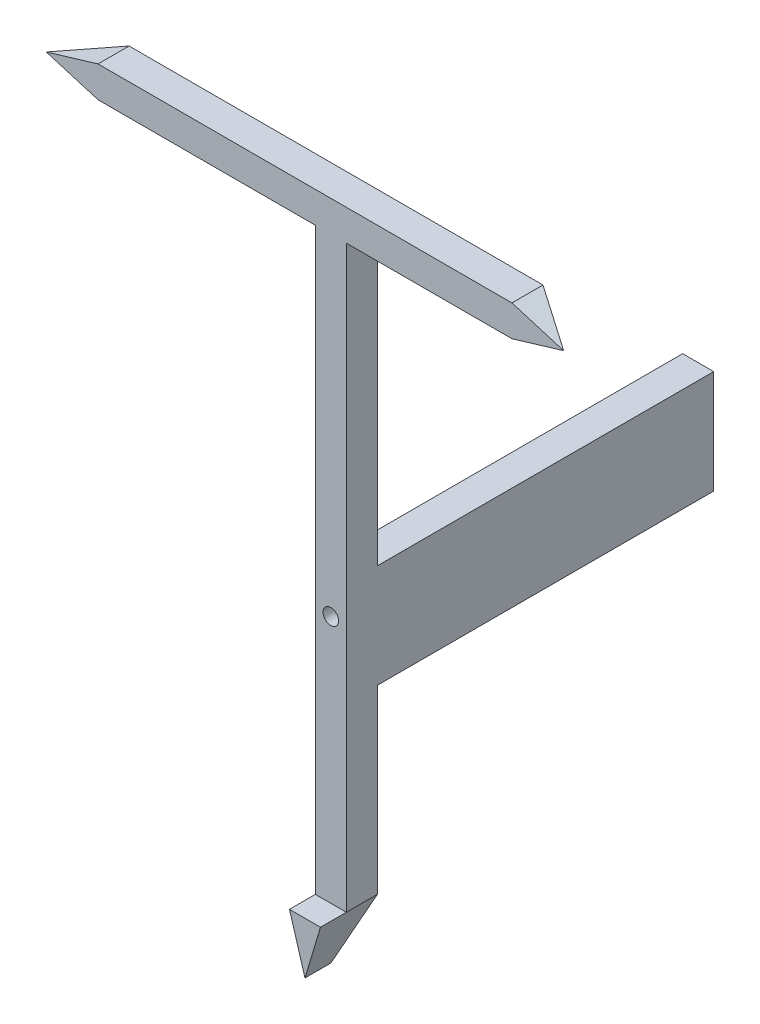
SolidWorks part; units mm, degrees
ref_plane "Front Plane" through (0, 0, 0) normal (0, 0, 1) x (1, 0, 0)
ref_plane "Top Plane" through (0, 0, 0) normal (0, 1, 0) x (1, 0, 0)
ref_plane "Right Plane" through (0, 0, 0) normal (1, 0, 0) x (0, 0, -1)
sketch "Sketch1" plane through (0, 0, 0) normal (0, 0, 1) x (1, 0, 0)
  line L0 (-63.5, 0) -> (63.5, 0) construction
  line L1 (6.35, 0) -> (6.35, -158.75) construction
  line L2 (-63.5, 0) -> (-50.8, 3.81)
  line L3 (-50.8, 3.81) -> (50.8, 3.81)
  line L4 (50.8, 3.81) -> (63.5, 0)
  line L5 (63.5, 0) -> (50.8, -3.81)
  line L6 (50.8, -3.81) -> (10.16, -3.81)
  line L7 (-50.8, -3.81) -> (-63.5, 0)
  line L8 (6.35, -158.75) -> (2.54, -146.05)
  line L9 (6.35, -158.75) -> (10.16, -146.05)
  line L10 (2.54, -146.05) -> (2.54, -3.81)
  line L11 (10.16, -146.05) -> (10.16, -3.81)
  line L12 (2.54, -3.81) -> (-50.8, -3.81)
  circle A0 centre (6.35, -85.09) radius 1.905
  point P2 (0, 0)
  dimension "D12" = 3.81
  dimension "D1" = 127
  dimension "D2" = 69.85
  dimension "D3" = 158.75
  dimension "D4" = 12.7
  dimension "D5" = 12.7
  dimension "D6" = 7.62
  dimension "D7" = 3.81
  dimension "D8" = 12.7
  dimension "D9" = 7.62
  dimension "D10" = 3.81
  dimension "D11" = 88.9
ref_plane "Plane1" through (6.35, 0, 0) normal (1, 0, 0) x (0, 0, -1)
sketch "Sketch2" plane through (6.35, 0, 0) normal (1, 0, 0) x (0, 0, -1)
  line L0 (0, -158.75) -> (-6.35, -158.75)
  dimension "D1" = 6.35
extrude "Boss-Extrude1" add sketch "Sketch1" against normal blind 7.62
sketch "Sketch3" plane through (0, 3.81, 0) normal (0, 1, 0) x (1, 0, 0)
  line L0 (-63.5, 0) -> (-50.8, 7.62)
  line L1 (-50.8, 7.62) -> (-63.5, 7.62)
  line L2 (-63.5, 7.62) -> (-63.5, 0)
  line L3 (63.5, 7.62) -> (63.5, 0)
  line L4 (63.5, 0) -> (50.8, 7.62)
  line L5 (50.8, 7.62) -> (63.5, 7.62)
extrude "Cut-Extrude1" cut sketch "Sketch3" against normal through all
sketch "Sketch4" plane through (10.16, 0, 0) normal (1, 0, 0) x (0, 0, -1)
  line L0 (0, -158.75) -> (7.62, -146.05)
  line L1 (7.62, -146.05) -> (7.62, -158.75)
  line L2 (7.62, -158.75) -> (0, -158.75)
extrude "Cut-Extrude2" cut sketch "Sketch4" against normal through all
sketch "Sketch6" plane through (0, 0, 0) normal (0, 0, 1) x (1, 0, 0)
  line L0 (2.54, -146.05) -> (10.16, -146.05)
  line L1 (10.16, -146.05) -> (6.35, -158.75)
  line L2 (6.35, -158.75) -> (2.54, -146.05)
extrude "Boss-Extrude3" add sketch "Sketch6" along normal up to vertex (6.35 mm away) up to point (6.35, -158.75, 6.35)
sketch "Sketch7" plane through (2.54, 0, 0) normal (-1, 0, 0) x (0, 0, 1)
  line L0 (-7.62, -3.81) -> (-7.62, -146.05) construction
  line L1 (-7.62, -76.2) -> (-90.17, -76.2)
  line L2 (-7.62, -76.2) -> (-7.62, -101.6)
  line L3 (-7.62, -101.6) -> (-90.17, -101.6)
  line L4 (-90.17, -76.2) -> (-90.17, -101.6)
  point P6 (-7.62, -88.9)
  dimension "D1" = 88.9
  dimension "D2" = 82.55
  dimension "D3" = 25.4
extrude "Boss-Extrude4" add sketch "Sketch7" against normal up to surface (7.62 mm away) up to face at (10.16, -74.93, -3.81)
sketch "Sketch8" plane through (0, 0, -7.62) normal (0, 0, 1) x (1, 0, 0)
  circle A1 centre (6.35, -85.09) radius 1.905
  circle A2 centre (6.35, -85.09) radius 1.905
  dimension "D1" = 0
extrude "Cut-Extrude3" cut sketch "Sketch8" against normal through all both and the other way through all
